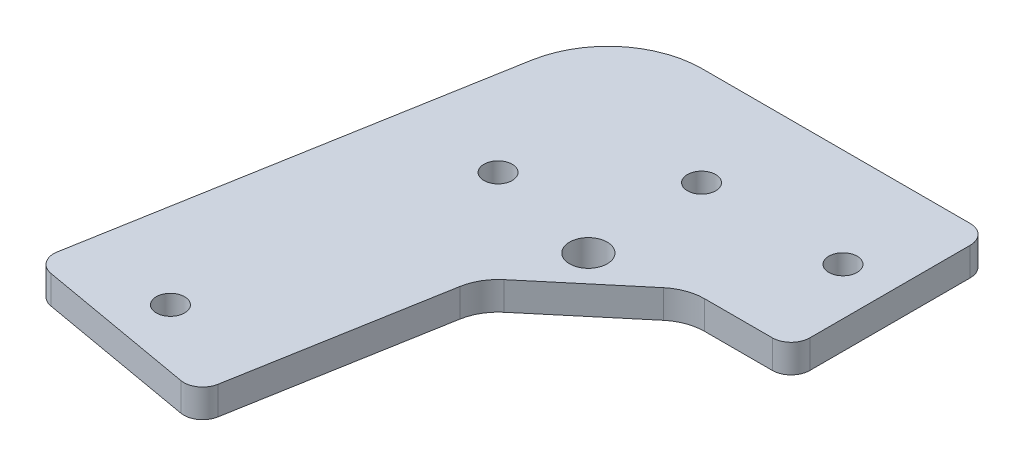
SolidWorks part; units mm, degrees
material "Thornel Mat VMA"
ref_plane "前视基准面" through (0, 0, 0) normal (0, 0, 1) x (1, 0, 0)
ref_plane "上视基准面" through (0, 0, 0) normal (0, 1, 0) x (1, 0, 0)
ref_plane "右视基准面" through (0, 0, 0) normal (1, 0, 0) x (0, 0, -1)
sketch "草图1" plane through (0, 0, 0) normal (0, 1, 0) x (1, 0, 0)
  line L0 (0, 0) -> (25, 0) construction
  line L1 (0, 0) -> (-6.9459, -39.3923) construction
  line L2 (30, -10.5) -> (20.8385, -10.5)
  line L3 (17.6245, -11.6698) -> (8.432, -19.3832)
  line L4 (30, -10.5) -> (30, 10.5)
  line L5 (30, 10.5) -> (-0.4195, 10.5)
  line L6 (-10.2676, 2.2365) -> (-18.1546, -42.493)
  line L7 (-18.1546, -42.493) -> (2.5263, -46.1397)
  line L8 (6.7219, -22.3452) -> (2.5263, -46.1397)
  line L10 (13.0283, -15.5265) -> (-6.8474, 8.1604) construction
  circle A0 centre (25, 0) radius 1.5
  circle A1 centre (10, 0) radius 1.5
  circle A2 centre (-6.9459, -39.3923) radius 1.5
  circle A3 centre (-1.7365, -9.8481) radius 1.5
  arc A4 (8.432, -19.3832) -> (6.7219, -22.3452) centre (11.646, -23.2135) ccw
  arc A5 (20.8385, -10.5) -> (17.6245, -11.6698) centre (20.8385, -15.5) ccw
  arc A6 (-0.4195, 10.5) -> (-10.2676, 2.2365) centre (-0.4195, 0.5) ccw
  circle A7 centre (10.4571, -12.4623) radius 2
  point P10 (-7.8142, -44.3163)
  point P17 (30, 0)
  point P26 (7.0379, -20.553)
  point P29 (19.0186, -10.5)
  dimension "D1" = 3
  dimension "D2" = 30
  dimension "D3" = 15
  dimension "D10" = 10
  dimension "D11" = 5
  dimension "D13" = 4
  dimension "D14" = 4
  dimension "D4" = 100
  dimension "D5" = 10
  dimension "D6" = 10
  dimension "D7" = 21
  dimension "D8" = 5
  dimension "D9" = 5
  dimension "D12" = 12
extrude "凸台-拉伸1" add sketch "草图1" along normal blind 3
fillet "圆角1" radius 2 4 edges at (30, 1.5, -10.5) (30, 1.5, 10.5) (2.5263, 1.5, 46.1397) (-18.1546, 1.5, 42.493)
